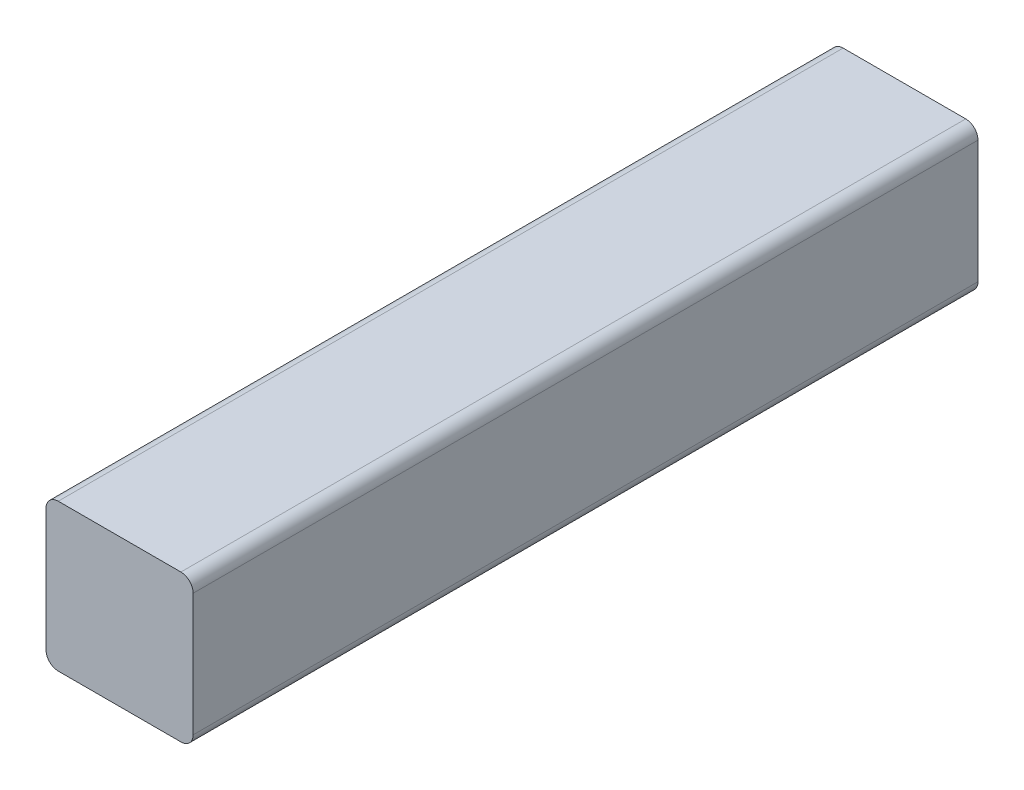
SolidWorks part; units mm, degrees
ref_plane "Front Plane" through (0, 0, 0) normal (0, 0, 1) x (1, 0, 0)
ref_plane "Top Plane" through (0, 0, 0) normal (0, 1, 0) x (1, 0, 0)
ref_plane "Right Plane" through (0, 0, 0) normal (1, 0, 0) x (0, 0, -1)
sketch "Sketch1" plane through (0, 0, 0) normal (0, 0, 1) x (1, 0, 0)
  line L1 (-19.05, -19.05) -> (19.05, -19.05)
  line L2 (-19.05, -19.05) -> (-19.05, 19.05)
  line L3 (-19.05, 19.05) -> (19.05, 19.05)
  line L4 (19.05, -19.05) -> (19.05, 19.05)
  line L5 (-19.05, -19.05) -> (19.05, 19.05) construction
  line L6 (-19.05, 19.05) -> (19.05, -19.05) construction
  point P0 (0, 0)
  dimension "D1" = 38.1
  dimension "D2" = 38.1
extrude "Boss-Extrude1" add sketch "Sketch1" along normal blind 203.2
fillet "Fillet1" radius 3.175 4 edges at (-19.05, 19.05, 101.6) (-19.05, -19.05, 101.6) (19.05, -19.05, 101.6) (19.05, 19.05, 101.6)
